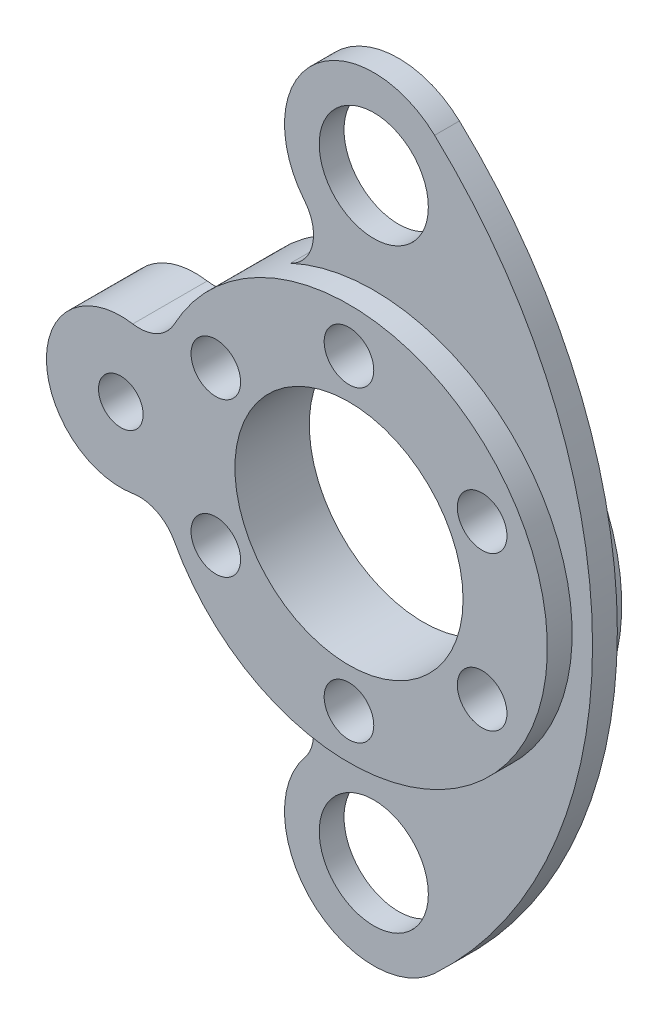
SolidWorks part; units mm, degrees
ref_plane "Front Plane" through (0, 0, 0) normal (0, 0, 1) x (1, 0, 0)
ref_plane "Top Plane" through (0, 0, 0) normal (0, 1, 0) x (1, 0, 0)
ref_plane "Right Plane" through (0, 0, 0) normal (1, 0, 0) x (0, 0, -1)
sketch "Sketch1" plane through (0, 0, 0) normal (0, 0, 1) x (1, 0, 0)
  line L0 (-67.0508, 0) -> (75.8645, 0) construction
  arc A0 (-35.2446, -18.9161) -> (-35.2446, 18.9161) centre (0, 0) ccw
  circle A1 centre (0, 0) radius 23
  circle A3 centre (-46, 0) radius 4.5
  arc A4 (-43.5827, 14.8039) -> (-43.5827, -14.8039) centre (-46, 0) ccw
  circle A6 centre (0, 0) radius 31
  circle A7 centre (0, 31) radius 5
  circle A8 centre (26.8468, 15.5) radius 5
  circle A9 centre (26.8468, -15.5) radius 5
  circle A10 centre (0, -31) radius 5
  circle A11 centre (-26.8468, -15.5) radius 5
  circle A12 centre (-26.8468, 15.5) radius 5
  arc A13 (-35.2446, -18.9161) -> (-43.5827, -14.8039) centre (-42.2935, -22.6994) ccw
  arc A14 (-43.5827, 14.8039) -> (-35.2446, 18.9161) centre (-42.2935, 22.6994) ccw
  point P29 (0, 0)
  dimension "D1" = 80
  dimension "D2" = 46
  dimension "D3" = 9
  dimension "D4" = 6
  dimension "D5" = 30
  dimension "D7" = 8
  dimension "D6" = 46
  dimension "D8" = 62
extrude "Boss-Extrude2" add sketch "Sketch1" against normal blind 15 contours A4 L0 A3 A6 A12 A7 A8 A0 A14 | L0 A4 A13 A0 A6 A9 A10 A11 A3 | A6 L0 A1 A8 A7 A12 | L0 A6 A11 A10 A9 A1
ref_plane "Plane1" through (0, 0, -7.5) normal (0, 0, 1) x (1, 0, 0)
sketch "Sketch2" plane through (0, 0, -7.5) normal (0, 0, 1) x (1, 0, 0)
  circle A0 centre (0, 60) radius 11
  circle A1 centre (0, 60) radius 18
  circle A2 centre (0, -60) radius 11
  circle A3 centre (0, -60) radius 18
  circle A4 centre (0, -31) radius 5 construction
  arc A7 (12.2691, -73.1707) -> (12.2691, 73.1707) centre (-55.8928, 0) ccw
  circle A8 centre (0, 0) radius 40
  arc A9 (-16.7901, 36.3056) -> (-13.9487, 48.6231) centre (-20.1481, 43.5667) ccw
  arc A10 (-13.9487, -48.6231) -> (-16.7901, -36.3056) centre (-20.1481, -43.5667) ccw
  dimension "D1" = 22
  dimension "D2" = 36
  dimension "D3" = 22
  dimension "D4" = 36
  dimension "D6" = 29
  dimension "D7" = 200
  dimension "D8" = 80
  dimension "D5" = 120
extrude "Boss-Extrude3" add sketch "Sketch2" along normal mid plane 5 contours A10 A3 A7 A1 A9 A8 | A1 A0 | A3 A2
